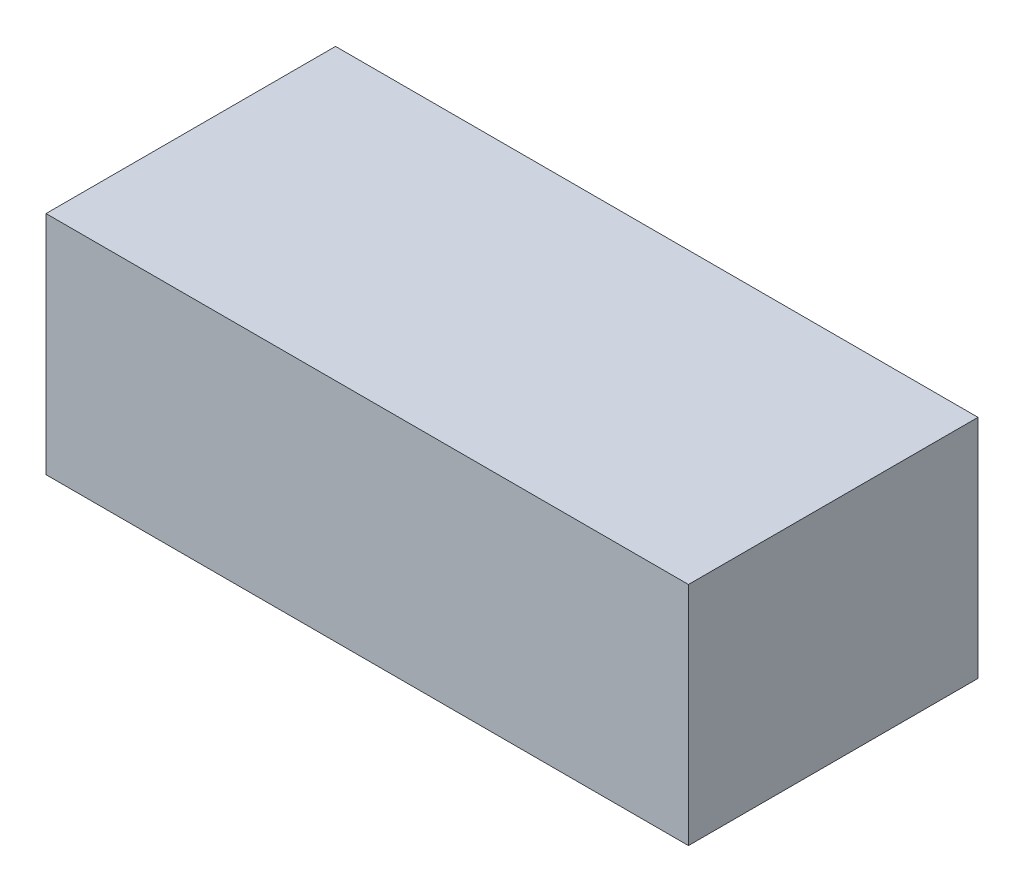
SolidWorks part; units mm, degrees
ref_plane "Front Plane" through (0, 0, 0) normal (0, 0, 1) x (1, 0, 0)
ref_plane "Top Plane" through (0, 0, 0) normal (0, 1, 0) x (1, 0, 0)
ref_plane "Right Plane" through (0, 0, 0) normal (1, 0, 0) x (0, 0, -1)
sketch "Sketch1" plane through (0, 0, 0) normal (1, 0, 0) x (0, 0, -1)
  line L1 (-16.9, 13.2) -> (16.9, 13.2)
  line L2 (-16.9, 13.2) -> (-16.9, -13.2)
  line L3 (-16.9, -13.2) -> (16.9, -13.2)
  line L4 (16.9, 13.2) -> (16.9, -13.2)
  point P4 (0, 13.2)
  point P6 (-16.9, 0)
  dimension "D1" = 33.8
  dimension "D2" = 26.4
extrude "Boss-Extrude1" add sketch "Sketch1" along normal blind 75
